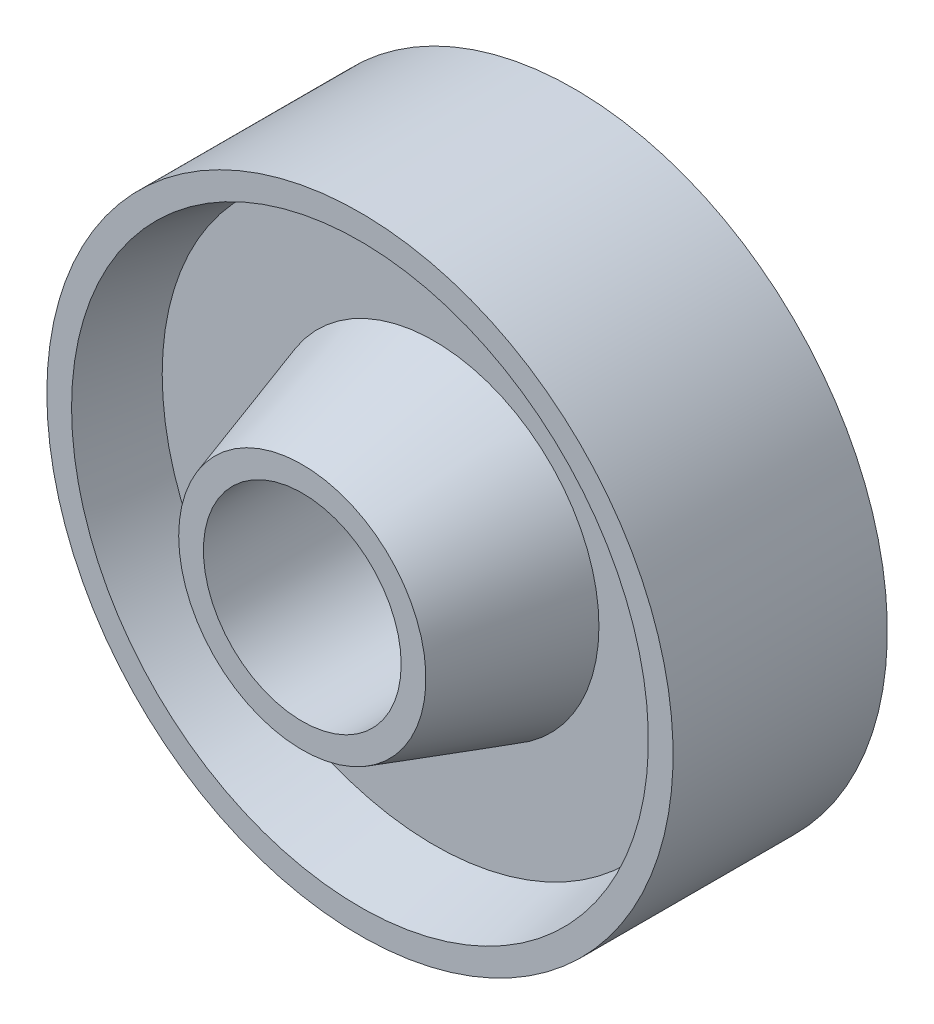
SolidWorks part; units mm, degrees
ref_plane "Front Plane" through (0, 0, 0) normal (0, 0, 1) x (1, 0, 0)
ref_plane "Top Plane" through (0, 0, 0) normal (0, 1, 0) x (1, 0, 0)
ref_plane "Right Plane" through (0, 0, 0) normal (1, 0, 0) x (0, 0, -1)
sketch "Sketch3" plane through (0, 0, 0) normal (0, 1, 0) x (1, 0, 0)
  line L0 (-57.7612, 0) -> (71.194, 0) construction
  line L1 (0, 47.3507) -> (0, -42.6493) construction
  line L2 (0, 20) -> (0, -20)
  line L3 (0, -20) -> (38, -20) construction
  line L4 (38, -20) -> (38, 20) construction
  line L5 (38, 20) -> (0, 20) construction
  line L6 (0, -20) -> (15, -20)
  line L7 (15, -20) -> (20, -4)
  line L8 (20, -4) -> (33, -4)
  line L9 (33, -4) -> (35, -13)
  line L10 (35, -13) -> (38, -13)
  line L11 (38, -13) -> (38, 13)
  line L12 (38, 13) -> (35, 13)
  line L13 (35, 13) -> (33, 4)
  line L14 (33, 4) -> (20, 4)
  line L15 (20, 4) -> (15, 20)
  line L16 (15, 20) -> (0, 20)
  dimension "D1" = 40
  dimension "D2" = 38
  dimension "D3" = 26
  dimension "D4" = 15
  dimension "D5" = 8
  dimension "D6" = 13
  dimension "D7" = 20
  dimension "D8" = 3
revolve "Revolve2" add sketch "Sketch3" angle 360 about L1
sketch "Sketch4" plane through (0, 0, 20) normal (0, 0, 1) x (1, 0, 0)
  circle A0 centre (0, 0) radius 12
  dimension "D1" = 24
extrude "Cut-Extrude1" cut sketch "Sketch4" against normal up to surface (40 mm away) up to face at (-15, 0, -20)
